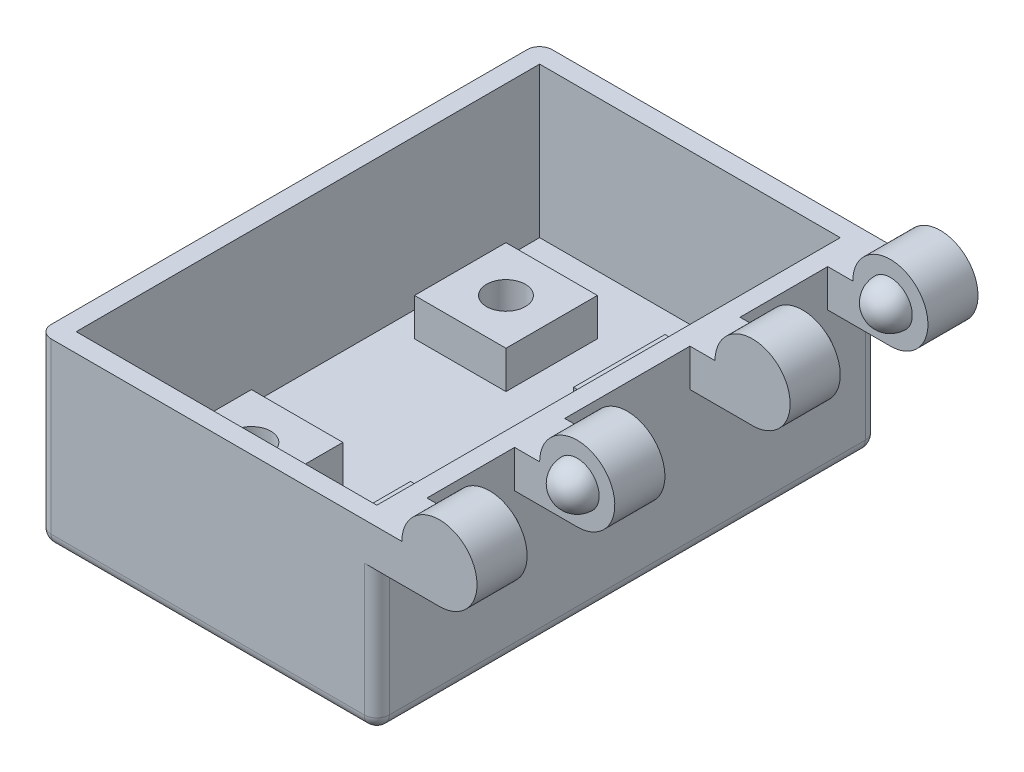
SolidWorks part; units mm, degrees
ref_plane "Front Plane" through (0, 0, 0) normal (0, 0, 1) x (1, 0, 0)
ref_plane "Top Plane" through (0, 0, 0) normal (0, 1, 0) x (1, 0, 0)
ref_plane "Right Plane" through (0, 0, 0) normal (1, 0, 0) x (0, 0, -1)
sketch "Sketch2" plane through (0, 0, 0) normal (0, 1, 0) x (1, 0, 0)
  line L1 (-13.5, -20) -> (13.5, -20)
  line L2 (-13.5, -20) -> (-13.5, 20)
  line L3 (-13.5, 20) -> (13.5, 20)
  line L4 (13.5, -20) -> (13.5, 20)
  line L5 (-13.5, -20) -> (13.5, 20) construction
  line L6 (-13.5, 20) -> (13.5, -20) construction
  point P0 (0, 0)
  dimension "D1" = 40
  dimension "D2" = 27
extrude "Boss-Extrude1" add sketch "Sketch2" along normal blind 2.5
sketch "Sketch3" plane through (0, 2.5, 0) normal (0, 1, 0) x (1, 0, 0)
  line L5 (-13.5, -20) -> (13.5, -20)
  line L6 (-13.5, -20) -> (-13.5, 20)
  line L7 (-12, 18.5) -> (12, 18.5)
  line L8 (-12, 18.5) -> (-12, -18.5)
  line L9 (-12, -18.5) -> (12, -18.5)
  line L10 (12, 18.5) -> (12, -18.5)
  line L11 (-12, 18.5) -> (12, -18.5) construction
  line L12 (-12, -18.5) -> (12, 18.5) construction
  line L13 (-13.5, 20) -> (13.5, 20)
  line L14 (13.5, -20) -> (13.5, 20)
  point P0 (0, 0)
  point P7 (0, 0)
  dimension "D1" = 1.5
  dimension "D2" = 1.5
extrude "Boss-Extrude2" add sketch "Sketch3" along normal blind 12
sketch "Sketch4" plane through (0, 0, 20) normal (0, 0, 1) x (1, 0, 0)
  line L0 (13.5, 14.5) -> (18.5, 14.5) construction
  line L1 (15.5, 14.5) -> (13.5, 14.5)
  line L2 (18.5, 11.5) -> (13.5, 11.5)
  line L3 (13.5, 14.5) -> (13.5, 0) construction
  line L4 (13.5, 11.5) -> (13.5, 14.5)
  arc A0 (18.5, 11.5) -> (15.5, 14.5) centre (18.5, 14.5) ccw
  dimension "D2" = 6
  dimension "D1" = 5
extrude "Boss-Extrude3" add sketch "Sketch4" against normal blind 4
sketch "Sketch5" plane through (0, 2.5, 0) normal (0, 1, 0) x (1, 0, 0)
  line L0 (0, 18.5) -> (0, -18.5) construction
  line L1 (-6.35, 10.16) -> (6.35, 10.16) construction
  line L2 (-6.35, 10.16) -> (-6.35, -10.16) construction
  line L3 (-6.35, -10.16) -> (6.35, -10.16) construction
  line L4 (6.35, 10.16) -> (6.35, -10.16) construction
  line L5 (-6.35, 10.16) -> (6.35, -10.16) construction
  line L6 (-6.35, -10.16) -> (6.35, 10.16) construction
  line L7 (-10, 13.81) -> (-2.7, 13.81)
  line L8 (-10, 13.81) -> (-10, 6.51)
  line L9 (-10, 6.51) -> (-2.7, 6.51)
  line L10 (-2.7, 13.81) -> (-2.7, 6.51)
  line L11 (-10, 13.81) -> (-2.7, 6.51) construction
  line L12 (-10, 6.51) -> (-2.7, 13.81) construction
  line L13 (12, 18.5) -> (-12, 18.5) construction
  line L14 (-12, -18.5) -> (12, -18.5) construction
  line L15 (-12, 0) -> (12, 0) construction
  line L16 (-12, 18.5) -> (-12, -18.5) construction
  line L17 (12, -18.5) -> (12, 18.5) construction
  line L18 (10, 6.51) -> (2.7, 6.51)
  line L19 (2.7, 13.81) -> (2.7, 6.51)
  line L20 (10, 13.81) -> (2.7, 13.81)
  line L21 (10, 13.81) -> (10, 6.51)
  line L22 (10, -13.81) -> (10, -6.51)
  line L23 (10, -13.81) -> (2.7, -13.81)
  line L24 (2.7, -13.81) -> (2.7, -6.51)
  line L25 (10, -6.51) -> (2.7, -6.51)
  line L26 (-10, -6.51) -> (-2.7, -6.51)
  line L27 (-2.7, -13.81) -> (-2.7, -6.51)
  line L28 (-10, -13.81) -> (-2.7, -13.81)
  line L29 (-10, -13.81) -> (-10, -6.51)
  point P0 (0, 0)
  dimension "D1" = 20.32
  dimension "D2" = 12.7
  dimension "D3" = 7.3
  dimension "D4" = 7.3
extrude "Boss-Extrude4" add sketch "Sketch5" along normal blind 3
sketch "Sketch6" plane through (0, 5.5, 0) normal (0, 1, 0) x (1, 0, 0)
  line L1 (-6.35, -10.16) -> (6.35, -10.16)
  line L2 (-6.35, -10.16) -> (-6.35, 10.16)
  line L3 (-6.35, 10.16) -> (6.35, 10.16)
  line L4 (6.35, -10.16) -> (6.35, 10.16)
  line L5 (-6.35, -10.16) -> (6.35, 10.16) construction
  line L6 (-6.35, 10.16) -> (6.35, -10.16) construction
  point P0 (0, 0)
  dimension "D1" = 20.32
  dimension "D2" = 12.7
hole_wizard "Ø3.0mm Dowel Hole1" positions "Sketch7" profile "Sketch8" hole size "Ø3.0" standard "BSI"
sketch "Sketch7" plane through (0, 5.5, 0) normal (0, 1, 0) x (1, 0, 0)
  point P0 (-6.35, 10.16)
  point P3 (6.35, 10.16)
  point P6 (6.35, -10.16)
  point P9 (-6.35, -10.16)
sketch "Sketch8" plane through (-6.35, 5.5, -10.16) normal (1, 0, 0) x (0, 0, 1)
  line L0 (0, 0) -> (0, 3.7313)
  line L1 (0, 3.7313) -> (1.55, 2.8)
  line L2 (1.55, 2.8) -> (1.55, 0)
  line L5 (1.55, 0) -> (0, 0)
  line L10 (0, 3.7313) -> (-1.55, 2.8) construction
  line L11 (0, -6.35) -> (0, 107.95) construction
  dimension "Hole Dia." = 3.1
  dimension "Hole Depth" = 2.8
  dimension "Drill Angle" = 118
sketch "Sketch9" plane through (0, 0, 0) normal (0, -1, 0) x (1, 0, 0)
  line L6 (-21.9, 14.4) -> (21.9, 14.4)
  line L11 (-21.9, 14.4) -> (-21.9, -14.4)
  line L12 (-21.9, -14.4) -> (21.9, -14.4)
  line L22 (21.9, 14.4) -> (21.9, -14.4)
  line L23 (-21.9, 14.4) -> (21.9, -14.4) construction
  line L24 (-21.9, -14.4) -> (21.9, 14.4) construction
  point P0 (0, 0)
  dimension "D1" = 43.8
  dimension "D2" = 28.8
extrude "Boss-Extrude5" [suppressed] add sketch "Sketch9" against normal blind 1.5
sketch "Sketch10" [suppressed] plane through (0, 1.5, 0) normal (0, 1, 0) x (1, 0, 0)
  line L1 (-17.5, 10) -> (17.5, 10)
  line L2 (-17.5, 10) -> (-17.5, -10)
  line L3 (-17.5, -10) -> (17.5, -10)
  line L4 (17.5, 10) -> (17.5, -10)
  line L5 (-17.5, 10) -> (17.5, -10) construction
  line L6 (-17.5, -10) -> (17.5, 10) construction
  point P0 (0, 0)
  dimension "D1" = 35
  dimension "D2" = 20
sketch "Sketch13" plane through (0, 0, 16) normal (0, 0, -1) x (-1, 0, 0)
  line L0 (-18.5, 11.5) -> (-18.5, 17.5) construction
  line L1 (-18.5, 16.25) -> (-18.5, 12.75)
  arc A0 (-15.5, 14.5) -> (-18.5, 11.5) centre (-18.5, 14.5) ccw construction
  arc A1 (-18.5, 12.75) -> (-18.5, 16.25) centre (-18.5, 14.5) ccw
  dimension "D1" = 3.5
revolve "Revolve1" add sketch "Sketch13" angle 180 about L0
sketch "Sketch14" plane through (13.5, 0, 0) normal (1, 0, 0) x (0, 0, -1)
  line L0 (-20, 0) -> (-12.5, 0)
  line L1 (-20, 0) -> (20, 0) construction
  line L2 (-12.5, 0) -> (-12.5, 14.5)
  line L3 (-16, 14.5) -> (20, 14.5) construction
  dimension "D1" = 7.5
ref_plane "Plane1" through (0, 0, 12.5) normal (0, 0, -1) x (-1, 0, 0)
mirror "Mirror1" about plane through (0, 0, 12.5) normal (0, 0, -1) of "Revolve1", "Boss-Extrude3"
sketch "Sketch15" plane through (13.5, 0, 0) normal (1, 0, 0) x (0, 0, -1)
  line L0 (-20, 0) -> (0, 0)
  line L1 (0, 0) -> (0, 14.5)
  line L2 (-5, 14.5) -> (20, 14.5) construction
ref_plane "Plane2" through (0, 0, 0) normal (0, 0, -1) x (-1, 0, 0)
mirror "Mirror2" about plane through (0, 0, 0) normal (0, 0, -1) of "Mirror1", "Revolve1", "Boss-Extrude3"
hole_wizard "M4 Clearance Hole1" [suppressed] positions "Sketch11" profile "Sketch12" hole size "M4" standard "ANSI Metric"
sketch "Sketch11" [suppressed] plane through (0, 1.5, 0) normal (0, 1, 0) x (1, 0, 0)
  point P0 (-17.5, 10)
  point P3 (-17.5, -10)
  point P6 (17.5, -10)
  point P9 (17.5, 10)
sketch "Sketch12" plane through (-17.5, 1.5, -10) normal (1, 0, 0) x (0, 0, 1)
  line L0 (0, 0) -> (0, 1.5)
  line L1 (0, 1.5) -> (2.4, 1.5)
  line L2 (2.4, 1.5) -> (2.4, 0)
  line L5 (2.4, 0) -> (0, 0)
  line L11 (0, -6.35) -> (0, 107.95) construction
  dimension "Thru Hole Dia." = 4.8
  dimension "Thru Hole Depth" = 1.5
fillet "Fillet1" radius 1 8 edges at (13.5, 5.75, -20) (-13.5, 7.25, -20) (-13.5, 7.25, 20) (13.5, 5.75, 20) (0, 0, -20) (-13.5, 0, 0) (0, 0, 20) (13.5, 0, 0)
